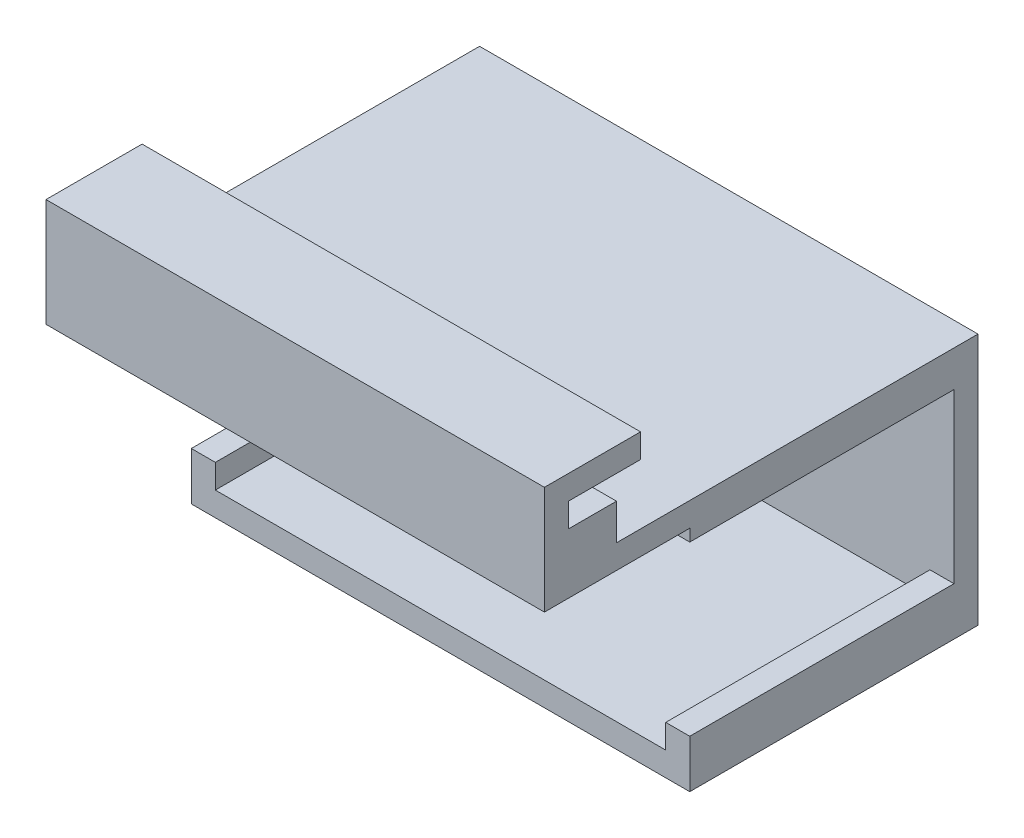
SolidWorks part; units mm, degrees
ref_plane "Alzado" through (0, 0, 0) normal (0, 0, 1) x (1, 0, 0)
ref_plane "Planta" through (0, 0, 0) normal (0, 1, 0) x (1, 0, 0)
ref_plane "Vista lateral" through (0, 0, 0) normal (1, 0, 0) x (0, 0, -1)
sketch "Croquis1" plane through (0, 0, 0) normal (0, 0, 1) x (1, 0, 0)
  line L0 (-48.9396, 26.5035) -> (-8.4396, 26.5035)
  line L2 (-48.9396, 26.5035) -> (-49.9396, 26.5035)
  line L3 (-8.4396, 6.5035) -> (-8.4396, 26.5035)
  line L5 (-8.4396, 6.5035) -> (-8.4396, 5.5035)
  line L6 (-48.9396, 5.5035) -> (-8.4396, 5.5035)
  line L7 (-49.9396, 26.5035) -> (-49.9396, 5.5035)
  line L8 (-49.9396, 5.5035) -> (-48.9396, 5.5035)
extrude "Saliente-Extruir1" add sketch "Croquis1" along normal blind 2
sketch "Croquis3" plane through (0, 0, 0) normal (0, 0, 1) x (1, 0, 0)
  line L0 (-48.9396, 26.5035) -> (-8.4396, 26.5035)
  line L1 (-46.9396, 7.5035) -> (-47.9396, 7.5035)
  line L2 (-48.9396, 5.5035) -> (-8.4396, 5.5035)
  line L3 (-8.4396, 6.5035) -> (-8.4396, 26.5035)
  line L4 (-46.9396, 24.5035) -> (-10.4396, 24.5035)
  line L5 (-10.4396, 8.5035) -> (-10.4396, 24.5035)
  line L6 (-46.9396, 7.5035) -> (-10.4396, 7.5035)
  line L8 (-48.9396, 6.5035) -> (-8.4396, 6.5035) construction
  line L9 (-47.9396, 7.5035) -> (-47.9396, 24.5035)
  line L10 (-8.4396, 6.5035) -> (-8.4396, 5.5035)
  line L12 (-48.9396, 5.5035) -> (-49.9396, 5.5035)
  line L13 (-10.4396, 8.5035) -> (-10.4396, 7.5035)
  line L14 (-49.9396, 5.5035) -> (-49.9396, 26.5035)
  line L15 (-46.9396, 8.5035) -> (-10.4396, 8.5035) construction
  line L16 (-49.9396, 26.5035) -> (-48.9396, 26.5035)
  line L17 (-47.9396, 24.5035) -> (-46.9396, 24.5035)
  line L18 (-48.9396, 26.5035) -> (-48.9396, 6.5035) construction
  line L20 (-46.9396, 24.5035) -> (-46.9396, 8.5035) construction
  dimension "D1" = 2
extrude "Saliente-Extruir2" add sketch "Croquis3" along normal blind 24
sketch "Croquis4" plane through (0, 0, 0) normal (1, 0, 0) x (0, 0, -1)
  line L0 (-2, 9.5035) -> (-28.8385, 9.5035)
  line L2 (-28.8385, 9.5035) -> (-28.8385, 23.5035)
  line L3 (-2, 23.5035) -> (-28.8385, 23.5035)
  line L4 (-2, 9.5035) -> (-2, 23.5035)
extrude "Cortar-Extruir1" cut sketch "Croquis4" against normal blind 70.1
ref_plane "Plano1" through (0, 26.5035, 0) normal (0, 1, 0) x (1, 0, 0)
sketch "Croquis5" plane through (0, 26.5035, 0) normal (0, 1, 0) x (1, 0, 0)
  line L0 (-49.9396, -20.6072) -> (-8.4396, -20.6072)
  line L1 (-8.4396, -24) -> (-49.9396, -24) construction
  line L2 (-49.9396, -24) -> (-49.9396, 0) construction
  line L3 (-49.9396, -20.6072) -> (-49.9396, -36.1)
  line L5 (-48.9396, -36.1) -> (-8.4396, -36.1)
  line L6 (-8.4396, -36.1) -> (-8.4396, -24)
  line L7 (-8.4396, -24) -> (-8.4396, -20.6072)
  line L8 (-8.4396, -24) -> (-8.4396, 0) construction
  line L12 (-49.9396, -36.1) -> (-48.9396, -36.1)
extrude "Saliente-Extruir3" add sketch "Croquis5" against normal blind 2
ref_plane "Plano2" through (0, 0, 36.1) normal (0, 0, 1) x (1, 0, 0)
sketch "Croquis6" plane through (0, 0, 36.1) normal (0, 0, 1) x (1, 0, 0)
  line L0 (-8.4396, 24.5035) -> (-8.4396, 33.5035)
  line L3 (-8.4396, 24.5035) -> (-49.9396, 24.5035)
  line L4 (-48.9396, 33.5035) -> (-8.4396, 33.5035)
  line L5 (-49.9396, 24.5035) -> (-49.9396, 33.5035)
  line L6 (-49.9396, 33.5035) -> (-48.9396, 33.5035)
extrude "Saliente-Extruir4" add sketch "Croquis6" against normal blind 2
sketch "Croquis7" plane through (0, 0, 36.1) normal (0, 0, 1) x (1, 0, 0)
  line L0 (-8.4396, 31.5035) -> (-49.9396, 31.5035)
  line L2 (-49.9396, 33.5035) -> (-8.4396, 33.5035)
  line L3 (-8.4396, 33.5035) -> (-8.4396, 31.5035)
  line L4 (-8.4396, 24.5035) -> (-8.4396, 33.5035) construction
  line L5 (-49.9396, 24.5035) -> (-49.9396, 33.5035) construction
  line L6 (-49.9396, 31.5035) -> (-49.9396, 33.5035)
extrude "Saliente-Extruir5" add sketch "Croquis7" against normal blind 8
sketch "Croquis8" plane through (0, 0, 36.1) normal (0, 0, 1) x (1, 0, 0)
  line L0 (-49.9396, 29.5035) -> (-49.9396, 26.5035)
  line L2 (-49.715, 29.5035) -> (-8.4396, 29.5035)
  line L3 (-49.9396, 24.5035) -> (-49.9396, 33.5035) construction
  line L4 (-8.4396, 29.5035) -> (-8.4396, 26.5035)
  line L5 (-8.4396, 26.5035) -> (-49.715, 26.5035)
  line L7 (18.755, 26.5035) -> (-18.755, 26.5035) construction
  line L8 (-49.9396, 26.5035) -> (-49.715, 26.5035)
  line L9 (-49.715, 29.5035) -> (-49.9396, 29.5035)
extrude "Saliente-Extruir6" add sketch "Croquis8" against normal blind 6
